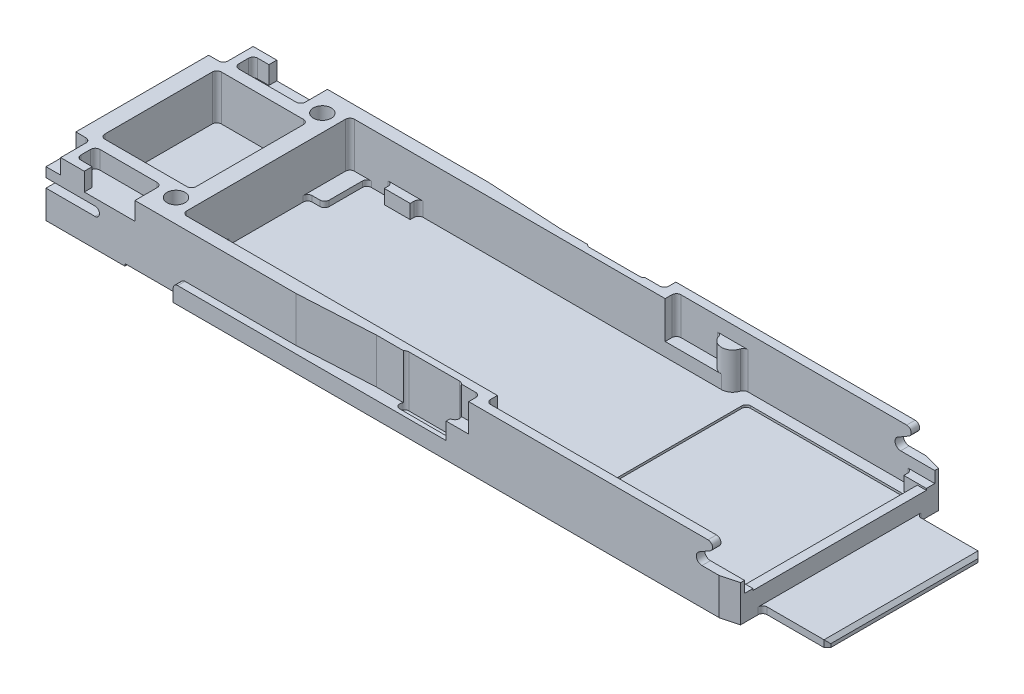
SolidWorks part; units mm, degrees
material "6063-T5"
ref_plane "Front Plane" through (0, 0, 0) normal (0, 0, 1) x (1, 0, 0)
ref_plane "Top Plane" through (0, 0, 0) normal (0, 1, 0) x (1, 0, 0)
ref_plane "Right Plane" through (0, 0, 0) normal (1, 0, 0) x (0, 0, -1)
sketch "Sketch1" plane through (0, 0, 0) normal (0, 1, 0) x (1, 0, 0)
  line L1 (-30.975, 9.2) -> (30.975, 9.2)
  line L2 (-30.975, 9.2) -> (-30.975, -9.2)
  line L3 (-30.975, -9.2) -> (30.975, -9.2)
  line L4 (30.975, 9.2) -> (30.975, -9.2)
  line L5 (-30.975, 9.2) -> (30.975, -9.2) construction
  line L6 (-30.975, -9.2) -> (30.975, 9.2) construction
  point P0 (0, 0)
  dimension "D1" = 61.95
  dimension "D2" = 18.4
extrude "Boss-Extrude1" add sketch "Sketch1" along normal blind 5.5
sketch "Sketch2" plane through (0, 5.5, 0) normal (0, 1, 0) x (1, 0, 0)
  line L0 (-30.975, 9.2) -> (-30.975, -9.2) construction
  line L1 (-19.975, 7.45) -> (-19.975, -7.45)
  line L2 (-19.975, -7.45) -> (8.025, -7.45)
  line L3 (8.025, -7.45) -> (8.025, -8.45)
  line L4 (8.025, -8.45) -> (30.975, -8.45)
  line L5 (30.975, -9.2) -> (30.975, 9.2) construction
  line L6 (30.975, -8.45) -> (30.975, 8.45)
  line L7 (30.975, 8.45) -> (8.025, 8.45)
  line L8 (8.025, 8.45) -> (8.025, 7.45)
  line L9 (8.025, 7.45) -> (-19.975, 7.45)
  line L10 (0, 0) -> (30.975, 0) construction
  dimension "D1" = 14.9
  dimension "D2" = 16.9
  dimension "D3" = 11
  dimension "D4" = 39
extrude "Cut-Extrude1" cut sketch "Sketch2" against normal blind 4.5
sketch "Sketch5" plane through (0, 5.5, 0) normal (0, 1, 0) x (1, 0, 0)
  line L0 (-19.975, 0) -> (-30.975, 0) construction
  line L1 (-29.525, 5.175) -> (-21.425, 5.175)
  line L2 (-29.525, 5.175) -> (-29.525, -5.175)
  line L3 (-29.525, -5.175) -> (-21.425, -5.175)
  line L4 (-21.425, 5.175) -> (-21.425, -5.175)
  line L5 (-29.525, 5.175) -> (-21.425, -5.175) construction
  line L6 (-29.525, -5.175) -> (-21.425, 5.175) construction
  line L7 (-19.975, 7.45) -> (-19.975, -7.45) construction
  line L8 (-30.975, 9.2) -> (-30.975, -9.2) construction
  point P0 (-25.475, 0)
  dimension "D1" = 10.35
  dimension "D2" = 8.1
extrude "Cut-Extrude2" cut sketch "Sketch5" against normal blind 4
hole_wizard "M2 Tapped Hole1" positions "Sketch7" profile "Sketch6" tap size "M2" standard "ISO" end condition through all
sketch "Sketch7" plane through (0, 5.5, 0) normal (0, 1, 0) x (-1, 0, 0)
  line L0 (0, 0) -> (30.975, 0) construction
  line L1 (30.975, -9.2) -> (30.975, 9.2) construction
  point P0 (21.475, -6.5)
  point P1 (21.475, 6.5)
  dimension "D1" = 13
  dimension "D2" = 9.5
sketch "Sketch6" plane through (-21.475, 5.5, -6.5) normal (1, 0, 0) x (0, 0, 1)
  line L0 (0, 0) -> (0, 5.5)
  line L1 (0, 5.5) -> (0.8, 5.5)
  line L2 (0.8, 5.5) -> (0.8, 0)
  line L5 (0.8, 0) -> (0, 0)
  line L11 (0, -6.35) -> (0, 107.95) construction
  dimension "Thru Tap Drill Dia." = 1.6
  dimension "Thru Tap Drill Depth" = 5.5
cosmetic thread "Hole Thread1" parameters "D2"=2
cosmetic thread "Hole Thread2" parameters "D2"=2
sketch "Sketch12" plane through (0, 5.5, 0) normal (0, 1, 0) x (1, 0, 0)
  line L0 (30.975, -8.45) -> (30.975, 8.45) construction
  line L1 (-30.975, 9.2) -> (-19.025, 9.2)
  line L2 (-30.975, 9.2) -> (-30.975, 8.55)
  line L3 (-30.975, 8.55) -> (-19.025, 8.55)
  line L4 (-19.025, 9.2) -> (-19.025, 8.55)
  dimension "D1" = 50
  dimension "D2" = 0.65
extrude "Cut-Extrude4" cut sketch "Sketch12" against normal through all
sketch "Sketch8" plane through (0, 5.5, 0) normal (0, 1, 0) x (1, 0, 0)
  line L1 (-23.075, 8.55) -> (-23.075, 6.175)
  line L2 (-23.075, 6.565) -> (-23.075, 8.55) construction
  line L3 (-23.075, 6.175) -> (-28.975, 6.175)
  line L4 (-28.975, 6.175) -> (-28.975, 7.85)
  line L5 (-28.975, 7.85) -> (-27.575, 7.85)
  line L6 (-27.575, 7.85) -> (-27.575, 8.55)
  line L7 (-27.575, 8.55) -> (-23.075, 8.55)
  line L9 (-21.425, 5.175) -> (-29.525, 5.175) construction
  line L10 (-30.975, 8.55) -> (-19.025, 8.55) construction
  line L11 (-30.975, 8.55) -> (-29.675, 8.55)
  line L12 (-30.975, 8.55) -> (-30.975, 5.9)
  line L13 (-30.975, 5.9) -> (-29.675, 5.9)
  line L14 (-29.675, 8.55) -> (-29.675, 5.9)
  line L15 (-30.975, 8.55) -> (-30.975, -9.2) construction
  dimension "D1" = 1.3
  dimension "D2" = 1
  dimension "D3" = 0.7
  dimension "D4" = 5.9
  dimension "D5" = 4.5
  dimension "D7" = 5.9
extrude "Cut-Extrude3" cut sketch "Sketch8" against normal blind 1.6
sketch "Sketch28" plane through (0, 3.9, 0) normal (0, 1, 0) x (1, 0, 0)
  line L0 (-29.675, 8.55) -> (-30.975, 8.55) construction
  line L1 (-29.675, 8.55) -> (-27.575, 8.55) construction
  line L2 (-30.975, 5.9) -> (-30.975, -9.2) construction
  line L3 (-30.975, 5.9) -> (-29.675, 5.9) construction
  line L4 (-29.675, 5.9) -> (-29.675, 8.55) construction
  line L8 (-30.975, 8.55) -> (-30.975, 5.9)
  line L9 (-30.975, 5.9) -> (-29.675, 5.9)
  line L10 (-29.675, 5.9) -> (-29.675, 8.55)
  line L11 (-29.675, 8.55) -> (-30.975, 8.55)
extrude "Boss-Extrude9" add sketch "Sketch28" along normal blind 0.25
sketch "Sketch13" plane through (0, 5.5, 0) normal (0, 1, 0) x (1, 0, 0)
  line L0 (-19.025, 9.2) -> (7.225, 9.2)
  line L1 (30.975, 9.2) -> (-19.025, 9.2) construction
  line L2 (7.225, 9.2) -> (7.225, 8.175)
  line L3 (7.225, 8.175) -> (-1.975, 8.175)
  line L4 (-1.975, 8.175) -> (-8.775, 8.55)
  line L5 (-8.775, 8.55) -> (-19.025, 8.55)
  line L6 (-19.025, 8.55) -> (-19.025, 9.2)
  line L8 (8.025, 8.45) -> (8.025, 7.45) construction
  dimension "D2" = 0.8
extrude "Cut-Extrude5" cut sketch "Sketch13" against normal offset from surface (4 mm away) 1.5 up to face at (-21.475, 0, -5.7)
sketch "Sketch15" plane through (-30.975, 0, 0) normal (-1, 0, 0) x (0, 0, 1)
  line L0 (-8.55, 0) -> (-8.55, 4.15) construction
  line L1 (-8.55, 2.5) -> (-7.05, 2.5)
  line L2 (-8.55, 2.5) -> (-8.55, 3.3)
  line L3 (-8.55, 3.3) -> (-7.05, 3.3)
  line L4 (-7.05, 2.5) -> (-7.05, 3.3)
  line L5 (-8.55, 0) -> (9.2, 0) construction
  dimension "D1" = 1.5
  dimension "D2" = 2.5
  dimension "D3" = 0.8
extrude "Cut-Extrude6" cut sketch "Sketch15" against normal blind 4.35
sketch "Sketch30" plane through (0, 0, -7.05) normal (0, 0, -1) x (-1, 0, 0)
  line L1 (26.625, 3.3) -> (30.975, 3.3)
  line L3 (26.625, 2.5) -> (30.975, 2.5)
  line L4 (30.975, 3.3) -> (30.975, 2.5)
  arc A0 (26.625, 3.3) -> (26.625, 2.5) centre (26.625, 2.9) ccw
extrude "Cut-Extrude13" cut sketch "Sketch30" along normal through all
sketch "Sketch16" plane through (0, 0, 0) normal (0, -1, 0) x (1, 0, 0)
  line L0 (-23.975, -8.55) -> (-23.975, -6.5)
  line L1 (-30.975, -8.55) -> (-19.025, -8.55) construction
  line L2 (-18.975, -6.5) -> (-18.975, -8.55)
  line L3 (-18.975, -8.55) -> (-23.975, -8.55)
  arc A0 (-23.975, -6.5) -> (-18.975, -6.5) centre (-21.475, -6.5) cw
  circle A1 centre (-21.475, -6.5) radius 0.8 construction
  dimension "D1" = 5
extrude "Cut-Extrude7" cut sketch "Sketch16" against normal blind 0.2
sketch "Sketch18" plane through (0, 0, 9.2) normal (0, 0, 1) x (1, 0, 0)
  line L0 (29.975, 5.5) -> (27.6939, 4.183)
  line L1 (-30.975, 5.5) -> (30.975, 5.5) construction
  line L2 (27.9439, 3.25) -> (30.975, 3.25)
  line L3 (30.975, 5.5) -> (30.975, 0) construction
  line L4 (30.975, 3.25) -> (30.975, 5.5)
  line L5 (30.975, 5.5) -> (29.975, 5.5)
  line L6 (-30.975, 0) -> (30.975, 0) construction
  arc A0 (27.6939, 4.183) -> (27.9439, 3.25) centre (27.9439, 3.75) ccw
  dimension "D4" = 0.5
  dimension "D1" = 1
  dimension "D2" = 3.25
  dimension "D3" = 30
extrude "Cut-Extrude9" cut sketch "Sketch18" against normal through all
fillet "Fillet1" radius 0.4 2 edges at (29.975, 5.5, -8.825) (29.975, 5.5, 8.825)
chamfer "Chamfer1" distance 1.5 angle 15 2 edges at (30.975, 1.625, -9.2) (30.975, 1.625, 9.2)
mirror "Mirror1" about plane through (0, 0, 0) normal (0, 0, 1) of "Boss-Extrude9", "Cut-Extrude6", "Cut-Extrude3", "Cut-Extrude4", "Cut-Extrude5", "Cut-Extrude7"
sketch "Sketch31" plane through (0, 0, 7.05) normal (0, 0, 1) x (1, 0, 0)
  line L3 (-30.975, 3.3) -> (-30.975, 2.5)
  line L4 (-26.625, 3.3) -> (-30.975, 3.3)
  line L5 (-30.975, 2.5) -> (-26.625, 2.5)
  line L6 (-30.975, 3.3) -> (-30.975, 2.5)
  line L7 (-26.625, 3.3) -> (-30.975, 3.3)
  line L8 (-30.975, 2.5) -> (-26.625, 2.5)
  arc A1 (-26.625, 2.5) -> (-26.625, 3.3) centre (-26.625, 2.9) ccw
  arc A2 (-26.625, 2.5) -> (-26.625, 3.3) centre (-26.625, 2.9) ccw
  dimension "D1" = 0
extrude "Cut-Extrude14" cut sketch "Sketch31" along normal through all
sketch "Sketch20" plane through (0, 1.5, 0) normal (0, 1, 0) x (1, 0, 0)
  line L1 (7.225, -8.175) -> (5.225, -8.175)
  line L2 (7.225, -8.175) -> (7.225, -9.2)
  line L3 (7.225, -9.2) -> (5.225, -9.2)
  line L4 (5.225, -8.175) -> (5.225, -9.2)
  line L5 (7.225, 8.175) -> (5.225, 8.175)
  line L6 (7.225, 8.175) -> (7.225, 9.2)
  line L7 (7.225, 9.2) -> (5.225, 9.2)
  line L8 (5.225, 8.175) -> (5.225, 9.2)
extrude "Boss-Extrude4" add sketch "Sketch20" along normal blind 1.5
sketch "Sketch22" plane through (0, 1.5, 0) normal (0, 1, 0) x (1, 0, 0)
  line L1 (0.725, 8.825) -> (5.225, 8.825) construction
  line L2 (5.225, 8.025) -> (0.725, 8.025) construction
  line L3 (5.225, -8.825) -> (0.725, -8.825) construction
  line L4 (5.225, -8.025) -> (0.725, -8.025) construction
  line L8 (0.725, 8.825) -> (5.225, 8.825)
  line L9 (5.225, 8.025) -> (0.725, 8.025)
  line L10 (5.225, -8.825) -> (0.725, -8.825)
  line L11 (5.225, -8.025) -> (0.725, -8.025)
  arc A0 (0.725, 8.825) -> (0.725, 8.025) centre (0.725, 8.425) ccw construction
  arc A1 (5.225, 8.025) -> (5.225, 8.825) centre (5.225, 8.425) ccw construction
  arc A2 (0.725, -8.025) -> (0.725, -8.825) centre (0.725, -8.425) ccw construction
  arc A3 (5.225, -8.825) -> (5.225, -8.025) centre (5.225, -8.425) ccw construction
  arc A4 (0.725, 8.825) -> (0.725, 8.025) centre (0.725, 8.425) ccw
  arc A5 (5.225, 8.025) -> (5.225, 8.825) centre (5.225, 8.425) ccw
  arc A6 (0.725, -8.025) -> (0.725, -8.825) centre (0.725, -8.425) ccw
  arc A7 (5.225, -8.825) -> (5.225, -8.025) centre (5.225, -8.425) ccw
extrude "Cut-Extrude11" cut sketch "Sketch22" against normal blind 0.55
sketch "Sketch23" plane through (0, 1, 0) normal (0, 1, 0) x (1, 0, 0)
  line L1 (-19.975, 7.45) -> (-18.475, 7.45)
  line L2 (-19.975, 7.45) -> (-19.975, 3.7)
  line L3 (-19.975, 3.7) -> (-18.475, 3.7)
  line L4 (-18.475, 7.45) -> (-18.475, 3.7)
  line L5 (-19.975, -7.45) -> (-18.475, -7.45)
  line L6 (-19.975, -7.45) -> (-19.975, -3.7)
  line L7 (-19.975, -3.7) -> (-18.475, -3.7)
  line L8 (-18.475, -7.45) -> (-18.475, -3.7)
  dimension "D1" = 7.4
  dimension "D2" = 1.5
extrude "Boss-Extrude5" add sketch "Sketch23" along normal blind 0.5
sketch "Sketch9" plane through (0, 0, 0) normal (0, -1, 0) x (1, 0, 0)
  line L0 (30.975, 8.45) -> (30.975, -8.45) construction
  line L1 (30.975, -6.84) -> (36.725, -6.84)
  line L2 (30.975, -6.84) -> (30.975, 6.84)
  line L3 (30.975, 6.84) -> (36.725, 6.84)
  line L4 (36.725, -6.84) -> (36.725, 6.84)
  line L5 (-30.975, -5.9) -> (-30.975, 5.9) construction
  line L6 (0, 0) -> (36.725, 0) construction
  point P13 (36.725, 6.84)
  point P16 (36.725, -6.84)
  dimension "D1" = 13.68
  dimension "D2" = 67.7
extrude "Boss-Extrude2" add sketch "Sketch9" against normal blind 0.6
chamfer "Chamfer2" distance 0.3 angle 45 3 edges at (36.725, 0.6, 0) (36.725, 0.3, -6.84) (36.725, 0.3, 6.84)
sketch "Sketch10" plane through (0, 0, 0) normal (0, 1, 0) x (1, 0, 0)
  line L0 (8.025, -8.45) -> (30.975, -8.45) construction
  line L1 (30.975, 8.45) -> (30.175, 8.45)
  line L2 (30.975, 8.45) -> (30.975, -8.45)
  line L3 (30.975, -8.45) -> (30.175, -8.45)
  line L4 (30.175, 8.45) -> (30.175, -8.45)
  dimension "D1" = 0.8
extrude "Boss-Extrude3" add sketch "Sketch10" along normal blind 2.1
sketch "Sketch24" plane through (0, 1, 0) normal (0, 1, 0) x (1, 0, 0)
  line L0 (8.025, 7.45) -> (-18.475, 7.45) construction
  line L1 (-16.175, 7.45) -> (-13.875, 7.45)
  line L2 (-16.175, 7.45) -> (-16.175, 6.7)
  line L3 (-16.175, 6.7) -> (-13.875, 6.7)
  line L4 (-13.875, 7.45) -> (-13.875, 6.7)
  line L5 (-18.475, -7.45) -> (8.025, -7.45) construction
  line L6 (-16.175, -7.45) -> (-13.875, -7.45)
  line L7 (-16.175, -7.45) -> (-16.175, -6.7)
  line L8 (-16.175, -6.7) -> (-13.875, -6.7)
  line L9 (-13.875, -7.45) -> (-13.875, -6.7)
  line L10 (-18.475, 3.7) -> (-18.475, 7.45) construction
  line L12 (30.975, 8.45) -> (28.975, 8.45)
  line L13 (30.975, 8.45) -> (30.975, 7.7)
  line L14 (30.975, 7.7) -> (28.975, 7.7)
  line L15 (28.975, 8.45) -> (28.975, 7.7)
  line L16 (30.975, -8.45) -> (28.975, -8.45)
  line L17 (30.975, -8.45) -> (30.975, -7.7)
  line L18 (30.975, -7.7) -> (28.975, -7.7)
  line L19 (28.975, -8.45) -> (28.975, -7.7)
  dimension "D1" = 13.4
  dimension "D2" = 2.3
  dimension "D3" = 2.3
  dimension "D4" = 2
extrude "Boss-Extrude6" add sketch "Sketch24" along normal blind 1.25
sketch "Sketch26" plane through (0, 1, 0) normal (0, 1, 0) x (1, 0, 0)
  line L0 (-19.975, -7.45) -> (8.025, -7.45) construction
  line L1 (8.025, 8.45) -> (13.025, 8.45)
  line L2 (8.025, 8.45) -> (8.025, 7.45)
  line L3 (8.025, 7.45) -> (13.025, 7.45)
  line L4 (13.025, 8.45) -> (13.025, 7.45)
  line L5 (8.025, -8.45) -> (11.025, -8.45)
  line L6 (8.025, -8.45) -> (8.025, -7.45)
  line L7 (8.025, -7.45) -> (11.025, -7.45)
  line L8 (11.025, -8.45) -> (11.025, -7.45)
  line L9 (8.025, 7.45) -> (-19.975, 7.45) construction
  dimension "D1" = 5
  dimension "D2" = 3
extrude "Boss-Extrude7" add sketch "Sketch26" along normal blind 1.2
sketch "Sketch27" plane through (0, 1, 0) normal (0, 1, 0) x (1, 0, 0)
  line L0 (13.025, 8.45) -> (8.025, 8.45) construction
  line L1 (28.975, 8.45) -> (13.025, 8.45) construction
  line L2 (13.025, 7.45) -> (13.025, 8.45) construction
  line L3 (12.025, 8.45) -> (14.025, 8.45)
  line L4 (8.025, -8.45) -> (28.4822, -8.45) construction
  line L5 (11.025, -8.45) -> (28.975, -8.45) construction
  line L6 (11.025, -8.45) -> (11.025, -7.45) construction
  line L7 (10.025, -8.45) -> (12.025, -8.45)
  arc A0 (12.025, 8.45) -> (14.025, 8.45) centre (13.025, 8.45) ccw
  arc A1 (10.025, -8.45) -> (12.025, -8.45) centre (11.025, -8.45) cw
extrude "Boss-Extrude8" add sketch "Sketch27" along normal offset from surface (3.25 mm away) 1.25 up to face at (-21.475, 5.5, -5.7)
sketch "Sketch19" plane through (0, 1, 0) normal (0, 1, 0) x (1, 0, 0)
  line L0 (30.175, -7.7) -> (30.175, 7.7) construction
  line L1 (30.175, 7.5) -> (15.175, 7.5)
  line L2 (30.175, 7.5) -> (30.175, -7.5)
  line L3 (30.175, -7.5) -> (15.175, -7.5)
  line L4 (15.175, 7.5) -> (15.175, -7.5)
  line L5 (0, 0) -> (15.175, 0) construction
  point P11 (30.175, -7.5)
  point P16 (30.175, 7.5)
  point P19 (15.175, 7.5)
  dimension "D1" = 15
  dimension "D2" = 15
extrude "Cut-Extrude10" cut sketch "Sketch19" against normal blind 0.2
sketch "Sketch29" plane through (0, 0.95, 0) normal (0, 1, 0) x (1, 0, 0)
  line L2 (0.725, 8.025) -> (5.225, 8.025)
  line L3 (5.225, 8.825) -> (0.725, 8.825)
  line L4 (0.725, 8.025) -> (5.225, 8.025)
  line L5 (5.225, 8.825) -> (0.725, 8.825)
  line L6 (5.225, -8.025) -> (0.725, -8.025)
  line L7 (0.725, -8.825) -> (5.225, -8.825)
  line L8 (5.225, -8.025) -> (0.725, -8.025)
  line L9 (0.725, -8.825) -> (5.225, -8.825)
  arc A2 (0.725, 8.825) -> (0.725, 8.025) centre (0.725, 8.425) ccw
  arc A3 (5.225, 8.025) -> (5.225, 8.825) centre (5.225, 8.425) ccw
  arc A4 (0.725, 8.825) -> (0.725, 8.025) centre (0.725, 8.425) ccw
  arc A5 (5.225, 8.025) -> (5.225, 8.825) centre (5.225, 8.425) ccw
  arc A6 (5.225, -8.825) -> (5.225, -8.025) centre (5.225, -8.425) ccw
  arc A7 (0.725, -8.025) -> (0.725, -8.825) centre (0.725, -8.425) ccw
  arc A8 (5.225, -8.825) -> (5.225, -8.025) centre (5.225, -8.425) ccw
  arc A9 (0.725, -8.025) -> (0.725, -8.825) centre (0.725, -8.425) ccw
  dimension "D1" = 0
  dimension "D2" = 0
extrude "Cut-Extrude12" cut sketch "Sketch29" along normal through all
fillet "Fillet2" radius 0.4 40 edges at (-23.075, 4.7, -6.175) (-28.975, 4.7, -7.85) (-28.975, 4.7, -6.175) (-29.675, 4.825, -5.9) (-29.675, 4.825, 5.9) (-23.075, 4.7, 6.175) (-28.975, 4.7, 6.175) (-28.975, 4.7, 7.85) (-29.525, 3.5, -5.175) (-21.425, 3.5, -5.175) (-21.425, 3.5, 5.175) (-29.525, 3.5, 5.175) (28.975, 1.625, -8.45) (28.975, 1.625, 8.45) (-13.875, 1.625, -7.45) (-16.175, 1.625, -7.45) (-18.475, 1.25, -7.45) (-19.975, 1.25, -3.7) (-16.175, 1.625, 7.45) (-13.875, 1.625, 7.45) (-19.975, 1.25, 3.7) (-18.475, 1.25, 7.45) (-19.975, 3.5, 7.45) (10.025, 3.225, 8.45) (12.025, 2.625, 8.45) (8.025, 3.85, 8.45) (14.025, 2.625, -8.45) (12.025, 3.225, -8.45) (8.025, 3.85, -8.45) (-19.975, 3.5, -7.45) (15.175, 0.9, 7.5) (15.175, 0.9, -7.5) (7.225, 4.25, 8.175) (7.225, 4.25, -8.175) (-19.025, 1.5, -8.875) (-19.025, 1.5, 8.875) (-18.475, 1.25, 3.7) (-18.475, 1.25, -3.7)
fillet "Fillet3" radius 0.4 2 edges
